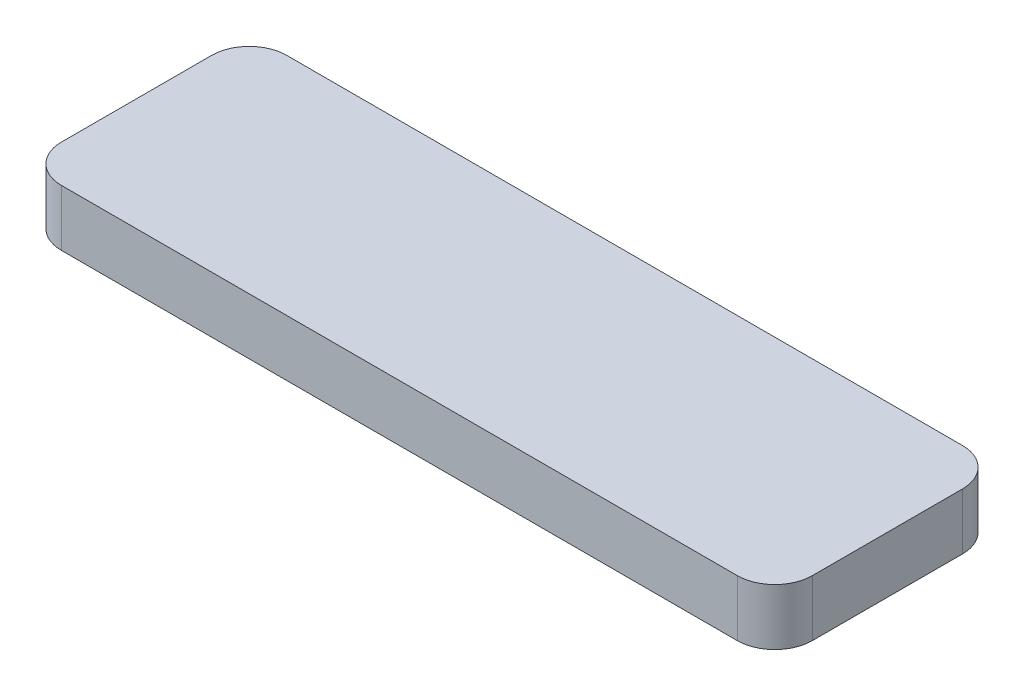
SolidWorks part; units mm, degrees
ref_plane "Plano frontal" through (0, 0, 0) normal (0, 0, 1) x (1, 0, 0)
ref_plane "Plano superior" through (0, 0, 0) normal (0, 1, 0) x (1, 0, 0)
ref_plane "Plano direito" through (0, 0, 0) normal (1, 0, 0) x (0, 0, -1)
sketch "Esboço1" plane through (0, 0, 0) normal (0, 1, 0) x (1, 0, 0)
  line L1 (-21.6233, 3.3086) -> (14.3767, 3.3086)
  line L2 (-23.6233, 1.3086) -> (-23.6233, -6.6914)
  line L3 (-21.6233, -8.6914) -> (14.3767, -8.6914)
  line L4 (16.3767, 1.3086) -> (16.3767, -6.6914)
  arc A0 (16.3767, -6.6914) -> (14.3767, -8.6914) centre (14.3767, -6.6914) cw
  arc A1 (16.3767, 1.3086) -> (14.3767, 3.3086) centre (14.3767, 1.3086) ccw
  arc A2 (-23.6233, -6.6914) -> (-21.6233, -8.6914) centre (-21.6233, -6.6914) ccw
  arc A3 (-23.6233, 1.3086) -> (-21.6233, 3.3086) centre (-21.6233, 1.3086) cw
  dimension "D1" = 2
extrude "Ressalto-extrusão1" add sketch "Esboço1" along normal blind 3
